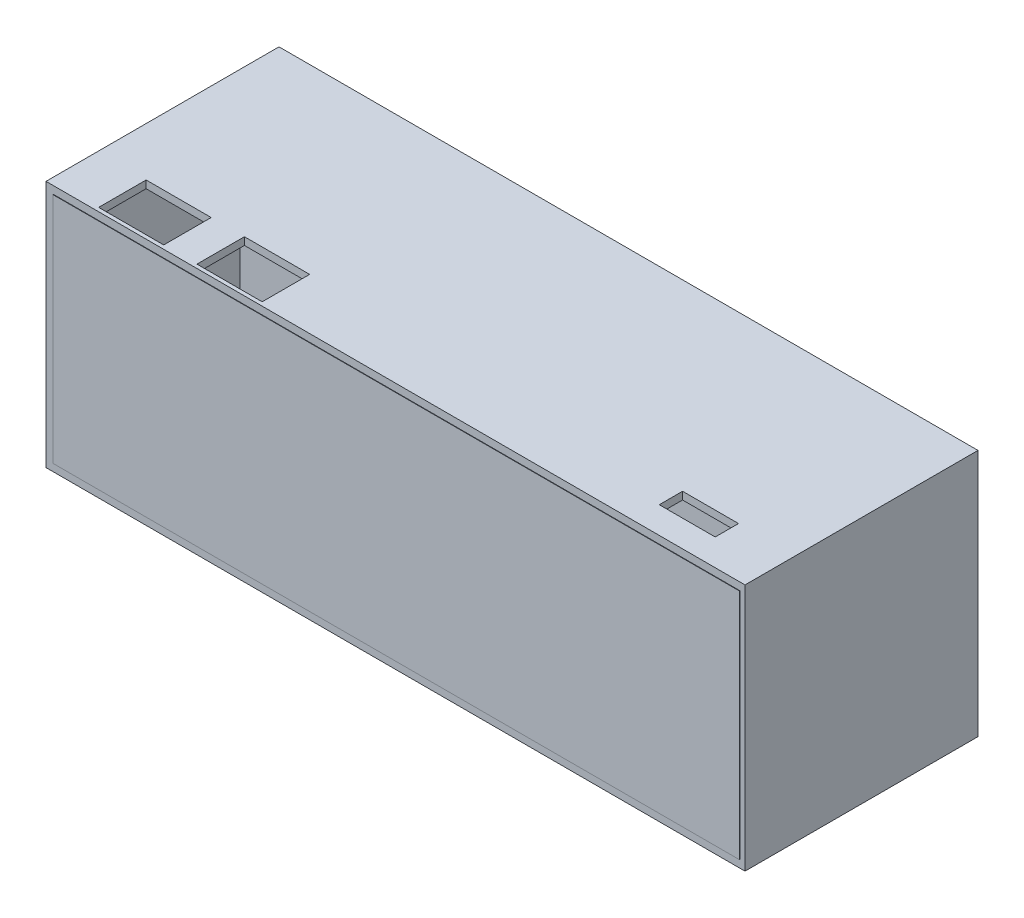
SolidWorks part; units mm, degrees
ref_plane "前视基准面" through (0, 0, 0) normal (0, 0, 1) x (1, 0, 0)
ref_plane "上视基准面" through (0, 0, 0) normal (0, 1, 0) x (1, 0, 0)
ref_plane "右视基准面" through (0, 0, 0) normal (1, 0, 0) x (0, 0, -1)
sketch "草图1" plane through (0, 0, 0) normal (0, 0, 1) x (1, 0, 0)
  line L0 (-32.5839, 32.768) -> (117.4161, 32.768)
  line L1 (117.4161, 32.768) -> (117.4161, -20.434)
  line L2 (117.4161, -20.434) -> (-32.5839, -20.434)
  line L3 (-32.5839, 32.768) -> (-32.5839, -20.434)
extrude "凸台-拉伸1" add sketch "草图1" along normal mid plane 50
sketch "草图2" plane through (0, 32.768, 0) normal (0, 1, 0) x (1, 0, 0)
  line L0 (-22.0949, -24.1874) -> (-22.0949, -14)
  line L1 (-1.0041, -24.1874) -> (-1.0041, -14)
  line L3 (-22.0949, -14) -> (-8.1343, -14)
  line L8 (-1.0041, -14) -> (12.9959, -14)
  line L12 (105.3127, -19.2924) -> (105.3127, -14.2924)
  line L13 (105.3127, -14.2924) -> (93.3127, -14.2924)
  line L14 (93.3127, -14.2924) -> (93.3127, -19.2924)
  line L15 (93.3127, -19.2924) -> (105.3127, -19.2924)
  line L16 (-8.1343, -24.1874) -> (-22.0949, -24.1874)
  line L17 (-8.1343, -14) -> (-8.1343, -24.1874)
  line L18 (12.9959, -14) -> (12.9959, -24.1874)
  line L19 (12.9959, -24.1874) -> (-1.0041, -24.1874)
sketch "草图3" plane through (0, 32.768, 0) normal (0, 1, 0) x (1, 0, 0)
extrude "切除-拉伸4" cut sketch "草图2" against normal through all both contours L17 L16 L0 L3 | L19 L1 L8 L18 | L12 L13 L14 L15
sketch "草图4" plane through (0, 0, 25) normal (0, 0, 1) x (1, 0, 0)
  line L0 (116.3235, 31.1429) -> (116.3235, -18.7942)
  line L6 (116.3235, -18.7942) -> (-30.954, -18.7942)
  line L11 (-30.954, -18.7942) -> (-30.954, 31.1429)
  line L12 (-30.954, 31.1429) -> (116.3235, 31.1429)
extrude "切除-拉伸9" cut sketch "草图4" against normal blind 40
sketch "草图6" plane through (0, 0, 25) normal (0, 0, 1) x (1, 0, 0)
  line L2 (-30.954, 31.1429) -> (116.3235, 31.1429)
  line L3 (116.3235, 31.1429) -> (116.3235, -18.7942)
  line L4 (116.3235, -18.7942) -> (-30.954, -18.7942)
  line L5 (-30.954, -18.7942) -> (-30.954, 31.1429)
extrude "凸台-拉伸2" add sketch "草图6" along normal blind 0.1 and the other way blind 2
sketch "草图7" plane through (0, 0, 23) normal (0, 0, -1) x (-1, 0, 0)
  circle A2 centre (-112.6987, 6.167) radius 0.5
  circle A3 centre (27.8664, 6.1744) radius 0.5
extrude "切除-拉伸11" cut sketch "草图7" against normal blind 0.1 and the other way through all
